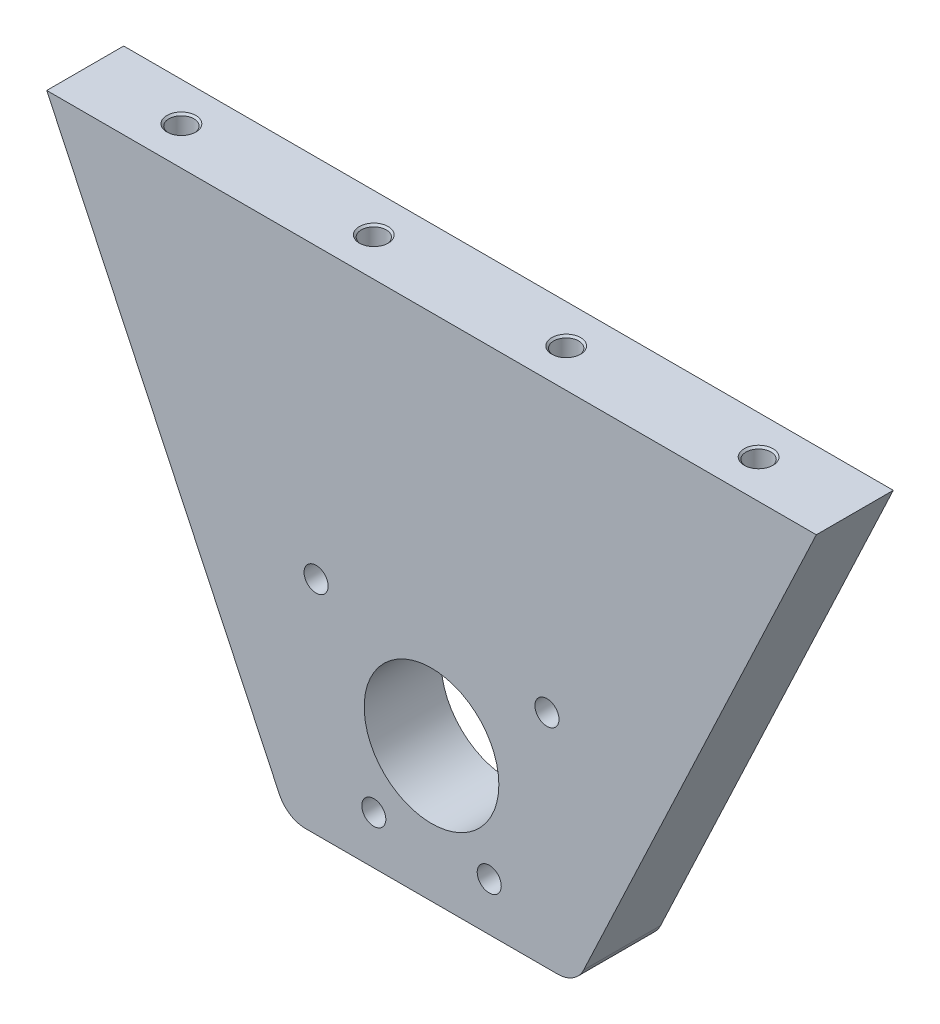
SolidWorks part; units mm, degrees
ref_plane "前基準面" through (0, 0, 0) normal (0, 0, 1) x (1, 0, 0)
ref_plane "上基準面" through (0, 0, 0) normal (0, 1, 0) x (1, 0, 0)
ref_plane "右基準面" through (0, 0, 0) normal (1, 0, 0) x (0, 0, -1)
sketch "草圖1" plane through (0, 0, 0) normal (0, 0, 1) x (1, 0, 0)
  line L0 (0, 0) -> (-6, 0) construction
  line L1 (0, 0) -> (6, 0) construction
  line L2 (0, 0) -> (0, 18) construction
  line L3 (0, 18) -> (-12, 18) construction
  line L4 (0, 18) -> (12, 18) construction
  line L5 (0, 0) -> (0, -5) construction
  line L6 (0, -5) -> (-13.0981, -5)
  line L7 (-15.8114, -3.2799) -> (-40, 48)
  line L8 (-40, 48) -> (0, 48)
  line L9 (0, 48) -> (40, 48)
  line L10 (40, 48) -> (15.8114, -3.2799)
  line L11 (13.0981, -5) -> (0, -5)
  line L12 (0, 18) -> (0, 48)
  circle A3 centre (6, 0) radius 1.25
  circle A4 centre (-6, 0) radius 1.25
  circle A6 centre (-12, 18) radius 1.25
  circle A7 centre (12, 18) radius 1.25
  arc A8 (13.0981, -5) -> (15.8114, -3.2799) centre (13.0981, -2) ccw
  arc A9 (-15.8114, -3.2799) -> (-13.0981, -5) centre (-13.0981, -2) ccw
  circle A10 centre (0, 9) radius 7
  point P20 (15, -5)
  point P23 (0, 9)
  dimension "D3" = 12
  dimension "D4" = 2.5
  dimension "D8" = 3
  dimension "D9" = 3
  dimension "D11" = 14
  dimension "D1" = 6
  dimension "D2" = 18
  dimension "D5" = 5
  dimension "D6" = 15
  dimension "D7" = 40
  dimension "D10" = 30
extrude "填料-伸長1" add sketch "草圖1" along normal blind 8
ref_plane "平面1" through (0, 48, 0) normal (0, 1, 0) x (1, 0, 0)
sketch "草圖2" plane through (0, 48, 0) normal (0, 1, 0) x (1, 0, 0)
  line L0 (0, 0) -> (0, -4) construction
  line L1 (0, -4) -> (-10, -4) construction
  line L2 (-10, -4) -> (-30, -4) construction
  line L3 (0, -4) -> (10, -4) construction
  line L4 (10, -4) -> (30, -4) construction
  circle A0 centre (-10, -4) radius 1.3
  circle A1 centre (-30, -4) radius 1.3
  circle A2 centre (10, -4) radius 1.3
  circle A3 centre (30, -4) radius 1.3
  dimension "D3" = 2.6
  dimension "D1" = 10
  dimension "D2" = 20
  dimension "D4" = 4
extrude "除料-伸長1" cut sketch "草圖2" against normal blind 7.5
chamfer "導角1" distance 0.2 4 edges at (-30, 48, 5.3) (30, 48, 5.3) (10, 48, 5.3) (-10, 48, 5.3)
